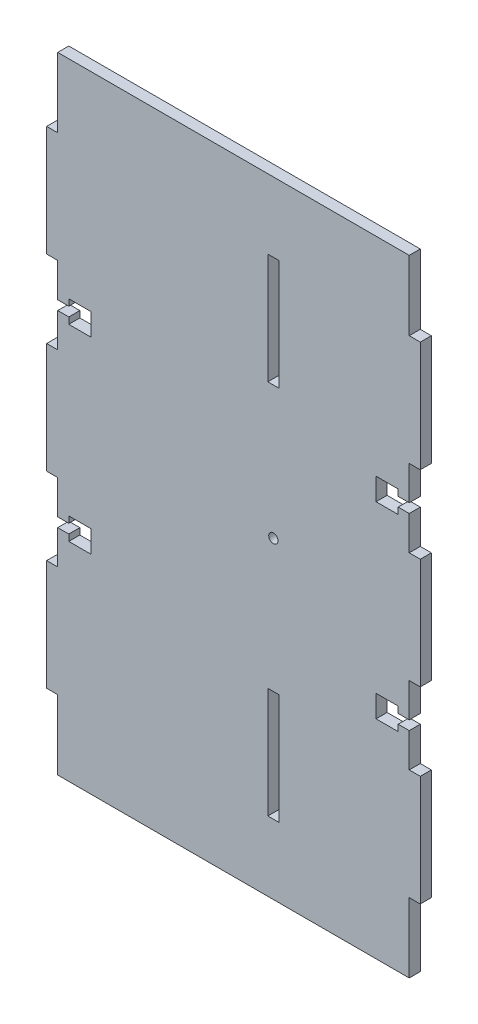
SolidWorks part; units mm, degrees
ref_plane "Plan de face" through (0, 0, 0) normal (0, 0, 1) x (1, 0, 0)
ref_plane "Plan de dessus" through (0, 0, 0) normal (0, 1, 0) x (1, 0, 0)
ref_plane "Plan de droite" through (0, 0, 0) normal (1, 0, 0) x (0, 0, -1)
sketch "Esquisse1" plane through (0, 0, 0) normal (0, 0, 1) x (1, 0, 0)
  line L0 (0, -3.53) -> (0, -35)
  line L1 (0, -35) -> (-5, -35)
  line L2 (-5, -35) -> (-5, -85)
  line L3 (-5, -85) -> (0, -85)
  line L4 (0, -85) -> (0, -100.4)
  line L5 (0, -120) -> (-5, -120)
  line L6 (-5, -120) -> (-5, -170)
  line L8 (-5, -60) -> (81.68, -60) construction
  line L9 (97.5, 0) -> (97.5, -290) construction
  line L10 (163.9185, -120) -> (163.9185, -170)
  line L11 (158.9185, -120) -> (163.9185, -120)
  line L12 (158.9185, -85) -> (158.9185, -100.4)
  line L13 (163.9185, -85) -> (158.9185, -85)
  line L14 (163.9185, -35) -> (163.9185, -85)
  line L15 (158.9185, -35) -> (163.9185, -35)
  line L16 (158.9185, -3.53) -> (158.9185, -35)
  line L17 (0, -170) -> (-5, -170)
  line L18 (0, -205) -> (0, -189.6)
  line L19 (-5, -205) -> (0, -205)
  line L20 (-5, -255) -> (-5, -205)
  line L21 (0, -255) -> (-5, -255)
  line L22 (0, -286.47) -> (0, -255)
  line L23 (158.9185, -286.47) -> (158.9185, -255)
  line L24 (158.9185, -255) -> (163.9185, -255)
  line L25 (163.9185, -255) -> (163.9185, -205)
  line L26 (163.9185, -205) -> (158.9185, -205)
  line L27 (158.9185, -205) -> (158.9185, -189.6)
  line L28 (158.9185, -170) -> (163.9185, -170)
  line L30 (0, -104.6) -> (5, -104.6)
  line L33 (0, -100.4) -> (5, -100.4)
  line L42 (0, -104.6) -> (0, -120)
  line L45 (0, -3.53) -> (158.9185, -3.53)
  line L48 (0, -185.4) -> (5, -185.4)
  line L56 (0, -189.6) -> (5, -189.6)
  line L57 (0, -185.4) -> (0, -170)
  line L62 (158.9185, -189.6) -> (153.9185, -189.6)
  line L65 (158.9185, -185.4) -> (153.9185, -185.4)
  line L71 (158.9185, -104.6) -> (153.9185, -104.6)
  line L79 (158.9185, -100.4) -> (153.9185, -100.4)
  line L80 (158.9185, -104.6) -> (158.9185, -120)
  line L81 (158.9185, -185.4) -> (158.9185, -170)
  line L82 (95, -35) -> (100, -35)
  line L83 (95, -35) -> (95, -85)
  line L84 (95, -85) -> (100, -85)
  line L85 (100, -35) -> (100, -85)
  line L90 (95, -205) -> (100, -205)
  line L91 (95, -205) -> (95, -255)
  line L92 (95, -255) -> (100, -255)
  line L93 (100, -205) -> (100, -255)
  line L94 (0, -286.47) -> (158.9185, -286.47)
  line L95 (97.5, -145) -> (66.3125, -145) construction
  line L96 (100, -230) -> (140, -230) construction
  line L97 (153.9185, -189.6) -> (153.9185, -192.5)
  line L98 (153.9185, -192.5) -> (143.9185, -192.5)
  line L99 (143.9185, -192.5) -> (143.9185, -182.5)
  line L100 (143.9185, -182.5) -> (153.9185, -182.5)
  line L101 (153.9185, -182.5) -> (153.9185, -185.4)
  line L102 (79.4592, -286.47) -> (79.4592, -265.8277) construction
  line L103 (143.9185, -97.5) -> (143.9185, -107.5)
  line L104 (143.9185, -107.5) -> (153.9185, -107.5)
  line L105 (153.9185, -107.5) -> (153.9185, -104.6)
  line L106 (153.9185, -97.5) -> (143.9185, -97.5)
  line L107 (153.9185, -100.4) -> (153.9185, -97.5)
  line L108 (15, -192.5) -> (15, -182.5)
  line L109 (5, -192.5) -> (15, -192.5)
  line L110 (15, -182.5) -> (5, -182.5)
  line L111 (5, -182.5) -> (5, -185.4)
  line L112 (5, -189.6) -> (5, -192.5)
  line L113 (5, -100.4) -> (5, -97.5)
  line L114 (5, -97.5) -> (15, -97.5)
  line L115 (15, -97.5) -> (15, -107.5)
  line L116 (15, -107.5) -> (5, -107.5)
  line L117 (5, -107.5) -> (5, -104.6)
  circle A0 centre (97.5, -145) radius 2.1
  point P34 (163.9185, -145)
  dimension "D13" = 4.2
  dimension "D16" = 2.9
  dimension "D17" = 10
  dimension "D18" = 10
  dimension "D2" = 5
  dimension "D3" = 50
  dimension "D4" = 35
  dimension "D5" = 5
  dimension "D6" = 5
  dimension "D7" = 86.68
  dimension "D8" = 2.5
  dimension "D12" = 5
  dimension "D14" = 2.5
  dimension "D15" = 100
extrude "Boss.-Extru.1" add sketch "Esquisse1" along normal blind 5
